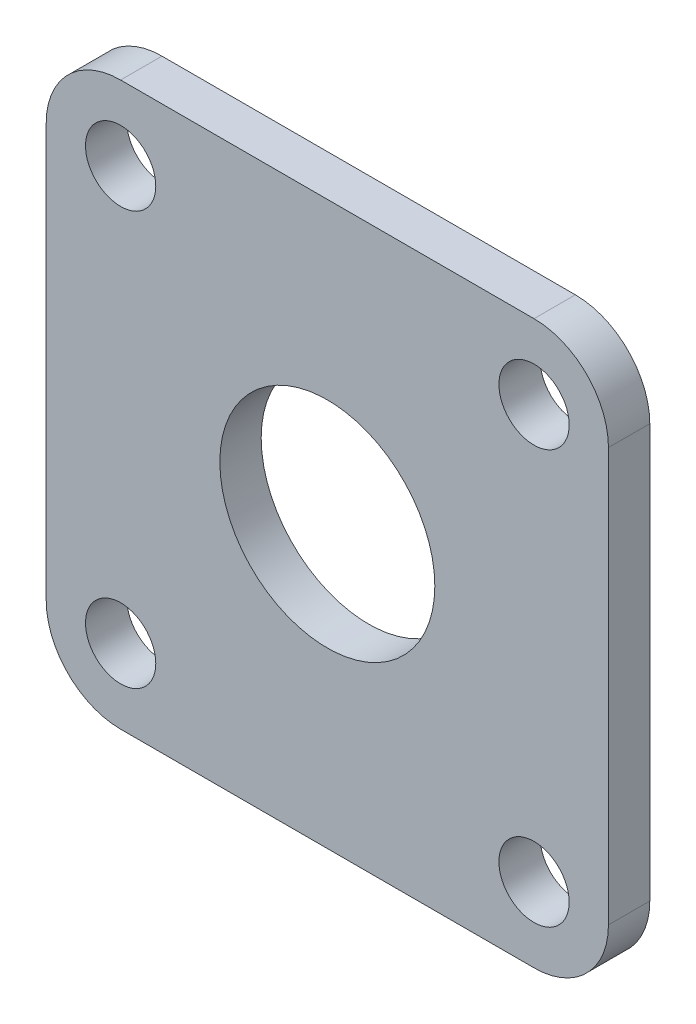
SolidWorks part; units mm, degrees
ref_plane "Alzado" through (0, 0, 0) normal (0, 0, 1) x (1, 0, 0)
ref_plane "Planta" through (0, 0, 0) normal (0, 1, 0) x (1, 0, 0)
ref_plane "Vista lateral" through (0, 0, 0) normal (1, 0, 0) x (0, 0, -1)
sketch "Croquis1" plane through (0, 0, 0) normal (0, 0, 1) x (1, 0, 0)
  line L1 (25, 34) -> (-25, 34)
  line L2 (34, 25) -> (34, -25)
  line L3 (25, -34) -> (-25, -34)
  line L4 (-34, 25) -> (-34, -25)
  line L5 (34, 34) -> (-34, -34) construction
  line L6 (34, -34) -> (-34, 34) construction
  arc A0 (25, 34) -> (34, 25) centre (25, 25) cw
  arc A1 (34, -25) -> (25, -34) centre (25, -25) cw
  arc A2 (-25, -34) -> (-34, -25) centre (-25, -25) cw
  arc A3 (-34, 25) -> (-25, 34) centre (-25, 25) cw
  circle A4 centre (-25, 25) radius 4.25
  circle A5 centre (-25, -25) radius 4.25
  circle A6 centre (25, -25) radius 4.25
  circle A7 centre (25, 25) radius 4.25
  circle A8 centre (0, 0) radius 13
  point P0 (0, 0)
  dimension "D3" = 9
  dimension "D4" = 8.5
  dimension "D5" = 8.5
  dimension "D6" = 8.5
  dimension "D7" = 8.5
  dimension "D8" = 26
  dimension "D1" = 68
  dimension "D2" = 68
extrude "Saliente-Extruir1" add sketch "Croquis1" along normal blind 5
